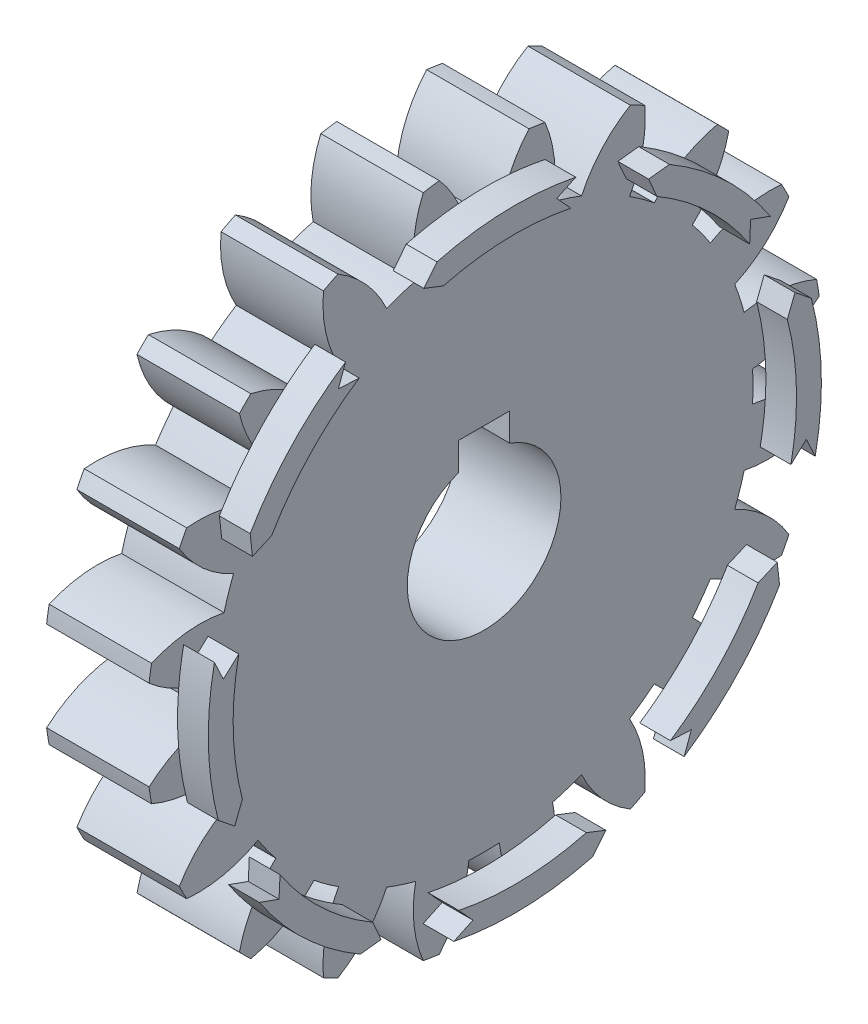
SolidWorks part; units mm, degrees
ref_plane "Plane1" through (0, 0, 0) normal (0, 0, 1) x (1, 0, 0)
ref_plane "Plane2" through (0, 0, 0) normal (0, 1, 0) x (1, 0, 0)
ref_plane "Plane3" through (0, 0, 0) normal (1, 0, 0) x (0, 0, -1)
sketch "HoldingSke" plane through (0, 0, 0) normal (0, 1, 0) x (1, 0, 0)
  line L0 (0, 0) -> (0.3132, -0.114)
  line L1 (-15, 0) -> (100, 0) construction
  line L2 (0, 0) -> (-2.1039, 2.3779)
  line L3 (0, 0) -> (-11.863, 4.5341)
  line L4 (0, 0) -> (8.1152, 2.9537)
  line L5 (0, 0) -> (-46.8476, -17.4728)
  line L6 (0, 0) -> (-8.2896, -5.593)
  line L7 (-2.1039, 2.3779) -> (8.6588, 51.2068)
  line L8 (-76.2, 54.61) -> (-73.9, 54.61)
  line L9 (-71.009, 38.7566) -> (-53.1078, 45.2721)
  line L10 (-76.2, 71.12) -> (104.1128, 71.12)
  line L11 (0, 0) -> (-10, 0)
  line L12 (-76.2, 101.6) -> (-76.093, 101.6)
  line L13 (24.9733, 27.94) -> (52.9518, 28.4284)
  line L14 (24.9733, 27.94) -> (24.9743, 27.94)
  line L15 (24.9733, 27.94) -> (100.4006, 29.5858)
  line L16 (-63.627, -3) -> (-12.827, -3)
  circle A0 centre (0, 0) radius 7.5
  circle A1 centre (0, 0) radius 24.0615
  circle A2 centre (0, 0) radius 37.5
  circle A3 centre (0, 0) radius 7.5
  dimension "MHD" = 48.123
  dimension "Hub_dia" = 75
  dimension "Bore" = 15
  dimension "MBD" = 15
  dimension "Num_teeth" = 20
  dimension "Pitch" = 0.3333
  dimension "Overall_len" = 50
  dimension "Show_teeth" = 20
  dimension "Thickness" = 10
  dimension "OAL" = 50.001
  dimension "T_dim" = 2.3
  dimension "Ap" = 20
  dimension "H" = 19.05
  dimension "Pitch_radius" = 180.3128
  dimension "Width" = 10
  dimension "Backlash" = 0.107
  dimension "Addendum_fac" = 1
  dimension "Dedendum_fac" = 1.25
  dimension "Clearance_fac" = 0.25
  dimension "Dedendum_add" = 0.001
  dimension "Module" = 3
sketch "BasProSke" plane through (0, 0, 0) normal (0, 1, 0) x (1, 0, 0)
  line L0 (-10, 0) -> (60, 0) construction
  line L1 (0, 0) -> (0, 33)
  line L2 (0, 0) -> (10, 0)
  line L3 (10, 0) -> (10, 33)
  line L4 (10, 33) -> (0, 33)
  dimension "Thickness" = 10
  dimension "Diameter" = 66
revolve "Base-Revolve" add sketch "BasProSke" angle 360 about L0
sketch "TooCutSke" plane through (0, 0, 0) normal (1, 0, 0) x (0, 0, -1)
  line L1 (0, 0) -> (0, 107) construction
  line L2 (0, 0) -> (-2.5409, 29.8922) construction
  line L3 (0, 0) -> (-9.3616, 59.1066) construction
  line L4 (-2.5409, 29.8922) -> (-4.6808, 29.5533) construction
  arc A0 (1.4893, 26.2067) -> (-1.4893, 26.2067) centre (0, 0) ccw
  arc A1 (4.4016, 32.7308) -> (-4.4016, 32.7308) centre (0, 0) ccw
  circle A2 centre (0, 0) radius 30 construction
  circle A3 centre (0, 0) radius 28.1908 construction
  arc A4 (-1.4893, 26.2067) -> (-4.4016, 32.7308) centre (-13.4064, 24.799) ccw
  arc A5 (4.4016, 32.7308) -> (1.4893, 26.2067) centre (13.4064, 24.799) ccw
  dimension "Root_dia" = 52.498
  dimension "Overcut_dia" = 66.0508
  dimension "Pitch_dia" = 60
  dimension "Base_dia" = 56.3816
  dimension "Flank_rad" = 12
  dimension "Half_ang" = 9
  dimension "Half_CT" = 2.1665
extrude "ToothCut" cut sketch "TooCutSke" along normal through all
fillet "Breaks" [suppressed] radius 0.06
fillet "RootFillets" [suppressed] radius 0.751
pattern_circular "TeethCuts" count 20 every 18 about axis through (-10, 0, 0) along (1, 0, 0) of "ToothCut", "RootFillets", "Breaks"
sketch "HubNeaOneSke" plane through (0, 0, 0) normal (-1, 0, 0) x (0, 0, 1)
  circle A0 centre (0, 0) radius 24.0615
  dimension "Diameter" = 48.123
extrude "HubNearOne" [suppressed] add sketch "HubNeaOneSke" along normal blind 40.001
sketch "HubNeaBotSke" plane through (0, 0, 0) normal (-1, 0, 0) x (0, 0, 1)
  circle A0 centre (0, 0) radius 24.0615
  dimension "Diameter" = 48.123
extrude "HubNearBoth" [suppressed] add sketch "HubNeaBotSke" along normal blind 20.0005
ref_plane "FarPln" through (10, 0, 0) normal (1, 0, 0) x (0, 0, -1)
sketch "HubFarSke" plane through (10, 0, 0) normal (1, 0, 0) x (0, 0, -1)
  circle A0 centre (0, 0) radius 24.0615
  dimension "Diameter" = 48.123
extrude "HubFar" [suppressed] add sketch "HubFarSke" along normal blind 20.0005
sketch "BorSke" plane through (0, 0, 0) normal (1, 0, 0) x (0, 0, -1)
  circle A0 centre (0, 0) radius 7.5
  dimension "Diameter" = 15
extrude "Bore" cut sketch "BorSke" along normal mid plane 100.0019
sketch "KeySke" plane through (0, 0, 0) normal (1, 0, 0) x (0, 0, -1)
  line L0 (-2.5, 0) -> (-2.5, 9.8)
  line L1 (-2.5, 9.8) -> (2.5, 9.8)
  line L2 (2.5, 9.8) -> (2.5, 0)
  line L3 (0, 0) -> (0, 34) construction
  line L4 (-2.5, 0) -> (2.5, 0)
  dimension "Offset" = 9.8
  dimension "Width" = 5
extrude "Keyway" cut sketch "KeySke" along normal mid plane 100.0019
pattern_circular "Keyway2" [suppressed] count 2 every 90 about axis through (-10, 0, 0) along (1, 0, 0)
sketch "Sketch1" plane through (10, 0, 0) normal (1, 0, 0) x (0, 0, -1)
  line L0 (0, 0) -> (-26.6618, 13.5887)
  line L1 (0, 0) -> (-25.8396, 15.0937)
  line L2 (-25.8396, 15.0937) -> (-25.615, 13.0551)
  line L3 (-25.615, 13.0551) -> (-23.7457, 13.8705)
  line L4 (0, 0) -> (-17.9318, 23.9574)
  line L5 (0, 0) -> (-16.53, 24.9453)
  line L6 (-16.53, 24.9453) -> (-17.2277, 23.0167)
  line L7 (-17.2277, 23.0167) -> (-15.1904, 22.9238)
  circle A0 centre (0, 0) radius 29.925
  circle A1 centre (0, 0) radius 27.5
  circle A2 centre (0, 0) radius 28.75
  dimension "D1" = 59.85
  dimension "D2" = 55
  dimension "D3" = 57.5
extrude "Boss-Extrude1" add sketch "Sketch1" along normal blind 3 contours L6 A0 L4 | A1 L7 L4 | A2 L4 A0 L1 | L4 A2 L1 A1 | A2 L1 L2 | L1 A2 L3
pattern_circular "CirPattern1" count 8 over 360 about axis through (0, 0, 0) along (1, 0, 0) of "Boss-Extrude1"
equation "' \"Module@HoldingSke\" = 6.35"
equation "' \"Num_teeth@HoldingSke\" = 12"
equation "' \"Ap@HoldingSke\" =  20"
equation "' \"Ap@HoldingSke\" = 20"
equation "' \"Width@HoldingSke\" = 0.5 * 25.4"
equation "' \"Hub_dia@HoldingSke\"= 1 * 25.4"
equation "' \"Hub_dia@HoldingSke\" = 1 * 25.4"
equation "' \"Overall_len@HoldingSke\" = 1.0 * 25.4"
equation "' \"Bore@HoldingSke\" = 0.75 * 25.4"
equation "' \"T_dim@HoldingSke\" = 0.1 * 25.4"
equation "' \"Width@KeySke\" = 0.25 * 25.4"
equation "' \"Show_teeth@HoldingSke\" = 13"
equation "' \"Backlash@HoldingSke\" = 0.009 * 25.4"
equation "' \"Addendum_fac@HoldingSke\" = 1.0"
equation "' \"Dedendum_fac@HoldingSke\" = 1.25"
equation "' \"Dedendum_add@HoldingSke\" = 0.00005 * 25.4"
equation "' \"Clearance_fac@HoldingSke\" = 0.25"
equation "\"Pitch@HoldingSke\" = 1 / \"Module@HoldingSke\""
equation "\"Overcut_dia@TooCutSke\" = (\"Num_teeth@HoldingSke\" + 2 * \"Addendum_fac@HoldingSke\") / \"Pitch@HoldingSke\" + 0.002 * 25.4"
equation "\"Pitch_dia@TooCutSke\" = \"Num_teeth@HoldingSke\" / \"Pitch@HoldingSke\""
equation "\"Base_dia@TooCutSke\" = \"Num_teeth@HoldingSke\" / \"Pitch@HoldingSke\" * cos((\"Ap@HoldingSke\"  * 3.14159265 / 180))"
equation "\"Root_dia@TooCutSke\" = (\"Num_teeth@HoldingSke\" + 2) / \"Pitch@HoldingSke\" - 2 * (\"Addendum_fac@HoldingSke\" + \"Dedendum_fac@HoldingSke\") / \"Pitch@HoldingSke\" - \"Dedendum_add@HoldingSke\" * 2"
equation "\"Half_ang@TooCutSke\" = 180 / \"Num_teeth@HoldingSke\""
equation "\"Half_CT@TooCutSke\" = \"Num_teeth@HoldingSke\" / \"Pitch@HoldingSke\" * sin((3.14159265 / 2 / \"Num_teeth@HoldingSke\")) / 2 - 7 * \"Backlash@HoldingSke\" / 4"
equation "\"Flank_rad@TooCutSke\" = \"Num_teeth@HoldingSke\" / \"Pitch@HoldingSke\" / 5"
equation "\"Radius@RootFillets\" = \"Clearance_fac@HoldingSke\" / \"Pitch@HoldingSke\" + \"Dedendum_add@HoldingSke\""
equation "\"Break_rad@Breaks\" = 0.02 / \"Pitch@HoldingSke\""
equation "\"Thickness@HoldingSke\" = \"Width@HoldingSke\""
equation "\"OAL@HoldingSke\" = \"Thickness@HoldingSke\""
equation "\"MHD@HoldingSke\" = (\"Num_teeth@HoldingSke\" + 2) / \"Pitch@HoldingSke\" - 2 * (\"Addendum_fac@HoldingSke\" + \"Dedendum_fac@HoldingSke\")  / \"Pitch@HoldingSke\" - \"Dedendum_add@HoldingSke\" * 2"
equation "\"MBD@HoldingSke\" = (\"Num_teeth@HoldingSke\" + 2) / \"Pitch@HoldingSke\" - 2 * (\"Addendum_fac@HoldingSke\" + \"Dedendum_fac@HoldingSke\")  / \"Pitch@HoldingSke\" - \"Dedendum_add@HoldingSke\" * 2 - 0.002 * 25.4"
equation "\"MHD@HoldingSke\" = ((sgn( \"MHD@HoldingSke\" - \"Hub_dia@HoldingSke\" )-1)*( \"MHD@HoldingSke\" - \"Hub_dia@HoldingSke\" ))/-2+ \"Hub_dia@HoldingSke\""
equation "\"MBD@HoldingSke\" = ((sgn( \"MBD@HoldingSke\" - \"Bore@HoldingSke\" )-1)*( \"MBD@HoldingSke\" - \"Bore@HoldingSke\" ))/-2+ \"Bore@HoldingSke\""
equation "\"OAL@HoldingSke\" = ((sgn( \"OAL@HoldingSke\" - \"Overall_len@HoldingSke\" )+1)*( \"OAL@HoldingSke\" - \"Overall_len@HoldingSke\" ))/2 + \"Overall_len@HoldingSke\" + 0.000002 * 25.4"
equation "\"Num_teeth@TeethCuts\" = int( \"Show_teeth@HoldingSke\" ) + 1"
equation "\"Num_teeth@TeethCuts\" = ((sgn( \"Num_teeth@TeethCuts\" - \"Num_teeth@HoldingSke\" )-1)*( \"Num_teeth@TeethCuts\" - \"Num_teeth@HoldingSke\" ))/-2+ \"Num_teeth@HoldingSke\""
equation "\"Num_teeth@TeethCuts\" = ((sgn( \"Num_teeth@TeethCuts\" - 2.0)+1)*( \"Num_teeth@TeethCuts\" - 2.0))/2 +2.0"
equation "\"Angle@TeethCuts\" = 360.0 / \"Num_teeth@HoldingSke\""
equation "\"Diameter@BasProSke\" = (\"Num_teeth@HoldingSke\" + 2 * \"Addendum_fac@HoldingSke\") / \"Pitch@HoldingSke\""
equation "\"Thickness@BasProSke\"  = \"Thickness@HoldingSke\""
equation "' \"Fillet_rad@BasProSke\" =  \"Thickness@HoldingSke\" * 0.05"
equation "' \"Fillet_rad@BasProSke\" = \"Thickness@HoldingSke\" * 0.05"
equation "\"MHD@HoldingSke\"= ( ( sgn ( \"MHD@HoldingSke\" - \"Root_dia@TooCutSke\" ) - 1 ) * ( \"MHD@HoldingSke\" - \"Root_dia@TooCutSke\" ) ) / - 2 + \"Root_dia@TooCutSke\""
equation "\"Diameter@HubNeaOneSke\" = \"MHD@HoldingSke\""
equation "\"Length@HubNearOne\" = \"OAL@HoldingSke\" - \"Thickness@BasProSke\""
equation "\"Diameter@HubNeaBotSke\" = \"MHD@HoldingSke\""
equation "\"Length@HubNearBoth\" = ( \"OAL@HoldingSke\" - \"Thickness@BasProSke\" ) / 2.0"
equation "\"Thickness@FarPln\" = \"Thickness@BasProSke\""
equation "\"Diameter@HubFarSke\" = \"MHD@HoldingSke\""
equation "\"Length@HubFar\" = ( \"OAL@HoldingSke\" - \"Thickness@BasProSke\" ) / 2.0"
equation "\"Diameter@BorSke\" = \"MBD@HoldingSke\""
equation "\"D1@Bore\" = \"OAL@HoldingSke\" * 2.0"
equation "\"D1@Keyway\" = \"OAL@HoldingSke\" * 2.0"
equation "\"Offset@KeySke\" = \"T_dim@HoldingSke\" + \"MBD@HoldingSke\" / 2.0"
